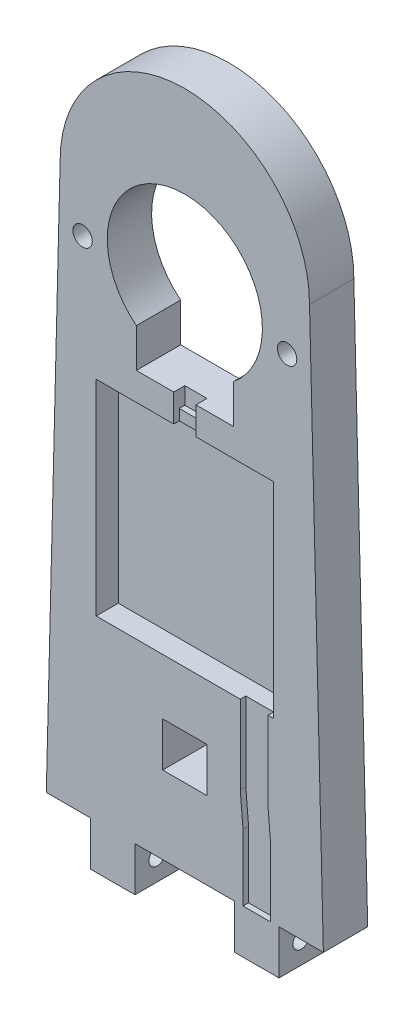
SolidWorks part; units mm, degrees
material "Acrylic (Medium-high impact)"
ref_plane "Front Plane" through (0, 0, 0) normal (0, 0, 1) x (1, 0, 0)
ref_plane "Top Plane" through (0, 0, 0) normal (0, 1, 0) x (1, 0, 0)
ref_plane "Right Plane" through (0, 0, 0) normal (1, 0, 0) x (0, 0, -1)
sketch "Sketch2" plane through (0, 0, 0) normal (0, 0, 1) x (1, 0, 0)
  line L0 (-22.5, 0) -> (-25, -100)
  line L1 (-25, -100) -> (0, -100)
  line L2 (25, -100) -> (22.5, 0)
  line L3 (0, -100) -> (25, -100)
  arc A0 (22.5, 0) -> (-22.5, 0) centre (0, 0) ccw
  circle A1 centre (0, 0) radius 2.5 construction
  dimension "D1" = 5
  dimension "D2" = 45
  dimension "D3" = 50
  dimension "D4" = 100
extrude "Arm Boss-Extrude1" add sketch "Sketch2" against normal blind 8
sketch "Sketch3" plane through (0, 0, 0) normal (0, 0, 1) x (1, 0, 0)
  line L0 (-8.75, -18.9287) -> (-8.75, -25.9287)
  line L1 (8.75, -18.9287) -> (8.75, -25.9287)
  line L2 (-8.75, -25.9287) -> (0, -25.9287)
  line L3 (0, -25.9287) -> (8.75, -25.9287)
  circle A0 centre (0, 0) radius 2.5 construction
  arc A1 (8.75, -18.9287) -> (-8.75, -18.9287) centre (0, -8) ccw
  dimension "D1" = 5
  dimension "D2" = 28
  dimension "D3" = 8
  dimension "D4" = 17.5
  dimension "D5" = 7
extrude "Stepper Cut-Extrude1" cut sketch "Sketch3" against normal up to surface (8 mm away) up to face at (0, -44.375, -8)
sketch "Sketch4" plane through (0, 0, 0) normal (0, 0, 1) x (1, 0, 0)
  line L0 (-2, -25.9287) -> (2, -25.9287)
  line L1 (-8.75, -25.9287) -> (8.75, -25.9287) construction
  line L2 (2, -25.9287) -> (2, -30.9287)
  line L3 (-2, -30.9287) -> (0, -30.9287)
  line L4 (-2, -30.9287) -> (-2, -25.9287)
  line L5 (0, -30.9287) -> (2, -30.9287)
  dimension "D1" = 4
  dimension "D2" = 5
extrude "Cable Cut-Extrude2" cut sketch "Sketch4" against normal blind 1
sketch "Sketch5" plane through (0, 0, 0) normal (0, 0, 1) x (1, 0, 0)
  line L0 (-16, -30.9287) -> (16, -30.9287)
  line L1 (16, -30.9287) -> (16, -67.9287)
  line L2 (-16, -30.9287) -> (-16, -67.9287)
  line L3 (-16, -67.9287) -> (0, -67.9287)
  line L4 (0, -67.9287) -> (16, -67.9287)
  line L6 (-2, -30.9287) -> (2, -30.9287) construction
  dimension "D1" = 37
  dimension "D2" = 32
extrude "ULN2003 Module Cut-Extrude3" cut sketch "Sketch5" against normal blind 4
sketch "Sketch6" plane through (0, -100, 0) normal (0, -1, 0) x (1, 0, 0)
  line L0 (-25, 0) -> (25, 0) construction
  line L1 (-17, 0) -> (-9, 0)
  line L2 (-17, 0) -> (-17, -8)
  line L3 (-17, -8) -> (-9, -8)
  line L4 (-9, 0) -> (-9, -8)
  line L5 (-25, -8) -> (25, -8) construction
  line L6 (-25, -8) -> (-25, 0) construction
  line L7 (17, 0) -> (9, 0)
  line L8 (17, 0) -> (17, -8)
  line L9 (17, -8) -> (9, -8)
  line L10 (9, 0) -> (9, -8)
  line L11 (25, -8) -> (25, 0) construction
  dimension "D1" = 8
  dimension "D2" = 8
extrude "Puzzle Slot Boss-Extrude2" add sketch "Sketch6" along normal blind 8
sketch "Sketch7" plane through (0, 0, 0) normal (0, 0, 1) x (1, 0, 0)
  line L0 (0, -8) -> (18.45, -8) construction
  line L1 (0, -8) -> (-18.45, -8) construction
  circle A0 centre (-18.45, -9.75) radius 1.75
  circle A1 centre (18.45, -9.75) radius 1.75
  arc A2 (8.75, -18.9287) -> (-8.75, -18.9287) centre (0, -8) ccw construction
  dimension "D2" = 3.5
  dimension "D1" = 36.9
extrude "Mounting Holes Cut-Extrude4" cut sketch "Sketch7" against normal up to surface (8 mm away) up to face at (0, -16.1966, -8)
sketch "Sketch8" plane through (-17, 0, 0) normal (-1, 0, 0) x (0, 0, 1)
  line L0 (-4, -100) -> (-4, -104) construction
  line L1 (0, -100) -> (-8, -100) construction
  line L2 (-4, -104) -> (-4, -108) construction
  line L3 (0, -108) -> (-8, -108) construction
  line L4 (-4, -104) -> (-8, -104) construction
  line L5 (-8, -108) -> (-8, -100) construction
  line L6 (-4, -104) -> (0, -104) construction
  line L7 (0, -108) -> (0, -100) construction
  circle A0 centre (-4, -104) radius 1.5
  dimension "D1" = 3
extrude "Puzzle Slot Screw Holes Cut-Extrude5" cut sketch "Sketch8" against normal up to surface (34 mm away) up to face at (17, -104, -4)
sketch "Sketch10" plane through (0, 0, -1) normal (0, 0, 1) x (1, 0, 0)
  line L0 (2, -30.9287) -> (2, -25.9287) construction
  line L1 (-2, -25.9287) -> (2, -25.9287)
  line L2 (-2, -25.9287) -> (-2, -28.9921)
  line L3 (-2, -28.9921) -> (2, -28.9921)
  line L4 (2, -25.9287) -> (2, -28.9921)
  line L5 (2, -30.9287) -> (2, -25.9287) construction
extrude "Cable Output Cut-Extrude6" cut sketch "Sketch10" against normal blind 1
sketch "Sketch11" plane through (0, 0, 0) normal (0, 0, 1) x (1, 0, 0)
  line L2 (-4, -86) -> (4, -86)
  line L3 (-9, -100) -> (9, -100) construction
  line L5 (0, -78) -> (4, -78)
  line L6 (4, -86) -> (4, -78)
  line L7 (0, -78) -> (-4, -78)
  line L10 (-4, -78) -> (-4, -86)
  dimension "D1" = 8
  dimension "D2" = 22
extrude "Side Puzzle Slot Cut-Extrude7" cut sketch "Sketch11" against normal up to surface (8 mm away) up to face at (20.2, -9.75, -8)
sketch "Sketch12" plane through (0, 0, 0) normal (0, 0, 1) x (1, 0, 0)
  line L0 (-9, -100) -> (9, -100) construction
  line L1 (-16, -67.9287) -> (16, -67.9287) construction
  line L2 (15, -67.9287) -> (10, -67.9287)
  line L3 (15, -67.9287) -> (15, -82.1031)
  line L4 (16, -67.9287) -> (16, -30.9287) construction
  line L5 (10.5, -100) -> (15.5, -100)
  line L6 (10.5, -100) -> (10.5, -88.0033)
  line L7 (10, -67.9287) -> (10, -82.1031)
  line L8 (9, -108) -> (9, -100) construction
  line L9 (15.5, -100) -> (15.5, -88.0033)
  line L10 (15.5, -88.0033) -> (15, -82.1031)
  line L12 (10, -82.1031) -> (10.5, -88.0033)
  dimension "D1" = 5
  dimension "D2" = 1
  dimension "D3" = 5
  dimension "D4" = 1.5
extrude "Cable Lower Cut-Extrude8" cut sketch "Sketch12" against normal blind 1
